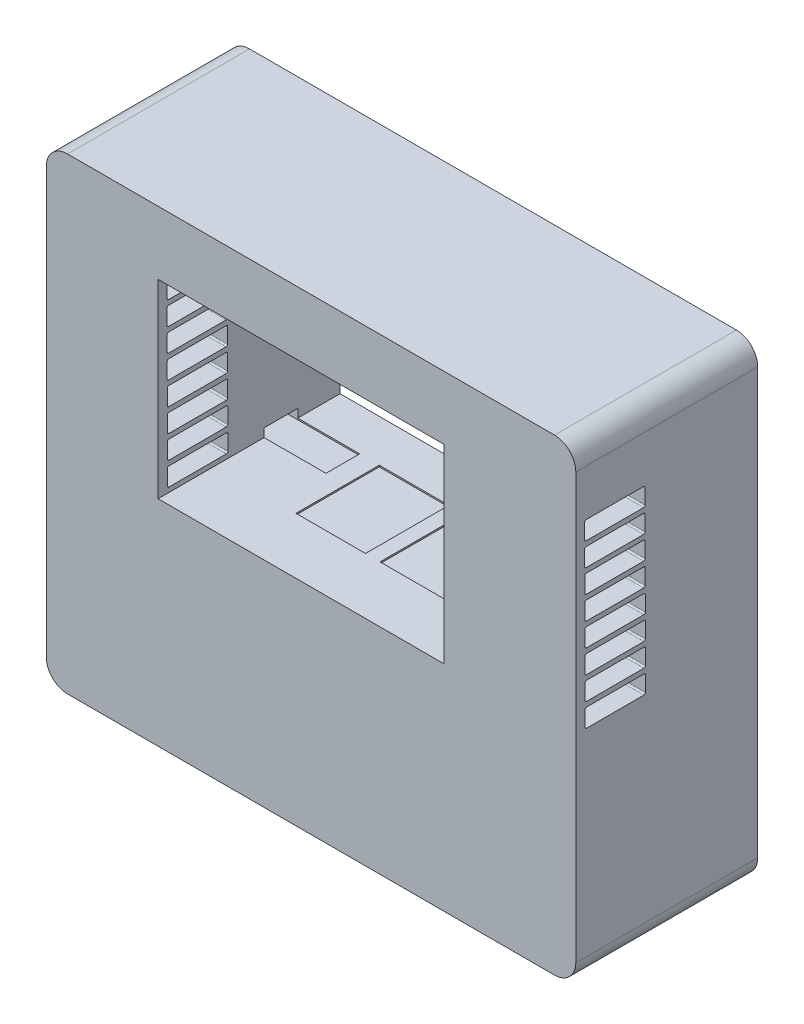
SolidWorks part; units mm, degrees
ref_plane "Front Plane" through (0, 0, 0) normal (0, 0, 1) x (1, 0, 0)
ref_plane "Top Plane" through (0, 0, 0) normal (0, 1, 0) x (1, 0, 0)
ref_plane "Right Plane" through (0, 0, 0) normal (1, 0, 0) x (0, 0, -1)
sketch "Sketch1" plane through (0, 0, 0) normal (0, 0, 1) x (1, 0, 0)
  line L4 (61.7, -0.1) -> (61.7, 38.3)
  line L5 (61.7, 38.3) -> (3.9, 38.3)
  line L6 (3.9, 38.3) -> (3.9, -0.1)
  line L7 (3.9, -0.1) -> (61.7, -0.1)
  line L8 (61.7, -0.1) -> (61.7, 38.3)
  line L9 (61.7, 38.3) -> (3.9, 38.3)
  line L10 (3.9, 38.3) -> (3.9, -0.1)
  line L11 (3.9, -0.1) -> (61.7, -0.1)
  line L12 (84, 51.09) -> (-14.4, 51.09)
  line L13 (-18.7, 46.79) -> (-18.7, -39.11)
  line L14 (-14.4, -43.41) -> (84, -43.41)
  line L15 (88.3, -39.11) -> (88.3, 46.79)
  line L16 (84, 51.09) -> (-14.4, 51.09)
  line L17 (-18.7, 46.79) -> (-18.7, -39.11)
  line L18 (-14.4, -43.41) -> (84, -43.41)
  line L19 (88.3, -39.11) -> (88.3, 46.79)
  arc A4 (88.3, 46.79) -> (84, 51.09) centre (84, 46.79) ccw
  arc A5 (-14.4, 51.09) -> (-18.7, 46.79) centre (-14.4, 46.79) ccw
  arc A6 (-18.7, -39.11) -> (-14.4, -43.41) centre (-14.4, -39.11) ccw
  arc A7 (84, -43.41) -> (88.3, -39.11) centre (84, -39.11) ccw
  arc A8 (88.3, 46.79) -> (84, 51.09) centre (84, 46.79) ccw
  arc A9 (-14.4, 51.09) -> (-18.7, 46.79) centre (-14.4, 46.79) ccw
  arc A10 (-18.7, -39.11) -> (-14.4, -43.41) centre (-14.4, -39.11) ccw
  arc A11 (84, -43.41) -> (88.3, -39.11) centre (84, -39.11) ccw
  dimension "D1" = 0
  dimension "D2" = 0
extrude "Boss-Extrude1" add sketch "Sketch1" against normal up to surface (36.766 mm away)
sketch "Sketch3" plane through (0, -0.4, 0) normal (0, -1, 0) x (1, 0, 0)
  line L0 (72.33, -24.7898) -> (72.33, -28.2198) construction
  line L1 (72.33, -28.2198) -> (81.22, -28.2198) construction
  line L2 (81.22, -28.2198) -> (81.22, -24.7898) construction
  line L3 (81.22, -24.7898) -> (72.33, -24.7898) construction
  line L4 (68.12, -28.296) -> (69.827, -28.296) construction
  line L5 (69.827, -28.296) -> (69.827, -14.646) construction
  line L6 (69.827, -14.646) -> (68.12, -14.646) construction
  line L7 (55.38, -28.296) -> (57.38, -28.296) construction
  line L8 (57.38, -14.646) -> (55.38, -14.646) construction
  line L9 (53.673, -14.646) -> (53.673, -28.296) construction
  line L10 (53.673, -28.296) -> (55.38, -28.296) construction
  line L11 (55.38, -14.646) -> (53.673, -14.646) construction
  line L12 (57.38, -28.296) -> (66.12, -28.296) construction
  line L13 (66.12, -14.646) -> (57.38, -14.646) construction
  line L14 (66.12, -28.296) -> (68.12, -28.296) construction
  line L15 (68.12, -14.646) -> (66.12, -14.646) construction
  line L16 (37.375, -11.3798) -> (37.375, -28.2198) construction
  line L17 (37.375, -28.2198) -> (51.425, -28.2198) construction
  line L18 (51.425, -28.2198) -> (51.425, -11.3798) construction
  line L19 (51.425, -11.3798) -> (37.375, -11.3798) construction
  line L20 (20.375, -11.3798) -> (20.375, -28.2198) construction
  line L21 (20.375, -28.2198) -> (34.425, -28.2198) construction
  line L22 (34.425, -28.2198) -> (34.425, -11.3798) construction
  line L23 (34.425, -11.3798) -> (20.375, -11.3798) construction
  line L24 (-1.288, -21.4098) -> (-1.288, -28.2198) construction
  line L25 (-1.288, -28.2198) -> (16.408, -28.2198) construction
  line L26 (16.408, -28.2198) -> (16.408, -21.4098) construction
  line L27 (16.408, -21.4098) -> (-1.288, -21.4098) construction
  line L28 (-13.85, -17.296) -> (-13.85, -28.296) construction
  line L29 (-13.85, -28.296) -> (-4.55, -28.296) construction
  line L30 (-4.55, -28.296) -> (-4.55, -17.296) construction
  line L31 (-4.55, -17.296) -> (-13.85, -17.296) construction
  line L32 (72.33, -24.7898) -> (72.33, -28.2198)
  line L33 (72.33, -28.2198) -> (81.22, -28.2198)
  line L34 (81.22, -28.2198) -> (81.22, -24.7898)
  line L35 (81.22, -24.7898) -> (72.33, -24.7898)
  line L36 (68.12, -28.296) -> (69.827, -28.296)
  line L37 (69.827, -28.296) -> (69.827, -14.646)
  line L38 (69.827, -14.646) -> (68.12, -14.646)
  line L39 (55.38, -28.296) -> (57.38, -28.296)
  line L40 (57.38, -14.646) -> (55.38, -14.646)
  line L41 (53.673, -14.646) -> (53.673, -28.296)
  line L42 (53.673, -28.296) -> (55.38, -28.296)
  line L43 (55.38, -14.646) -> (53.673, -14.646)
  line L44 (57.38, -28.296) -> (66.12, -28.296)
  line L45 (66.12, -14.646) -> (57.38, -14.646)
  line L46 (66.12, -28.296) -> (68.12, -28.296)
  line L47 (68.12, -14.646) -> (66.12, -14.646)
  line L48 (37.375, -11.3798) -> (37.375, -28.2198)
  line L49 (37.375, -28.2198) -> (51.425, -28.2198)
  line L50 (51.425, -28.2198) -> (51.425, -11.3798)
  line L51 (51.425, -11.3798) -> (37.375, -11.3798)
  line L52 (20.375, -11.3798) -> (20.375, -28.2198)
  line L53 (20.375, -28.2198) -> (34.425, -28.2198)
  line L54 (34.425, -28.2198) -> (34.425, -11.3798)
  line L55 (34.425, -11.3798) -> (20.375, -11.3798)
  line L56 (-1.288, -21.4098) -> (-1.288, -28.2198)
  line L57 (-1.288, -28.2198) -> (16.408, -28.2198)
  line L58 (16.408, -28.2198) -> (16.408, -21.4098)
  line L59 (16.408, -21.4098) -> (-1.288, -21.4098)
  line L60 (-13.85, -17.296) -> (-13.85, -28.296)
  line L61 (-13.85, -28.296) -> (-4.55, -28.296)
  line L62 (-4.55, -28.296) -> (-4.55, -17.296)
  line L63 (-4.55, -17.296) -> (-13.85, -17.296)
extrude "Cut-Extrude1" cut sketch "Sketch3" against normal blind 2
sketch "Sketch5" plane through (-18.7, 0, 0) normal (-1, 0, 0) x (0, 0, 1)
  line L0 (-1.8, 29.3) -> (-1.8, 32.4) construction
  line L1 (-13.7, 29) -> (-2.1, 29) construction
  line L2 (-14, 32.4) -> (-14, 29.3) construction
  line L3 (-2.1, 32.7) -> (-13.7, 32.7) construction
  line L4 (-1.8, 34) -> (-1.8, 37.1) construction
  line L5 (-13.7, 33.7) -> (-2.1, 33.7) construction
  line L6 (-14, 37.1) -> (-14, 34) construction
  line L7 (-2.1, 37.4) -> (-13.7, 37.4) construction
  line L8 (-1.8, 29.3) -> (-1.8, 32.4)
  line L9 (-13.7, 29) -> (-2.1, 29)
  line L10 (-14, 32.4) -> (-14, 29.3)
  line L11 (-2.1, 32.7) -> (-13.7, 32.7)
  line L12 (-1.8, 34) -> (-1.8, 37.1)
  line L13 (-13.7, 33.7) -> (-2.1, 33.7)
  line L14 (-14, 37.1) -> (-14, 34)
  line L15 (-2.1, 37.4) -> (-13.7, 37.4)
  line L16 (-1.8281, 19.9183) -> (-1.8281, 23.0183)
  line L17 (-13.7281, 19.6183) -> (-2.1281, 19.6183)
  line L18 (-14.0281, 23.0183) -> (-14.0281, 19.9183)
  line L19 (-2.1281, 23.3183) -> (-13.7281, 23.3183)
  line L20 (-1.8281, 24.6183) -> (-1.8281, 27.7183)
  line L21 (-13.7281, 24.3183) -> (-2.1281, 24.3183)
  line L22 (-14.0281, 27.7183) -> (-14.0281, 24.6183)
  line L23 (-2.1281, 28.0183) -> (-13.7281, 28.0183)
  line L24 (-1.8561, 10.5367) -> (-1.8561, 13.6367)
  line L25 (-13.7561, 10.2367) -> (-2.1561, 10.2367)
  line L26 (-14.0561, 13.6367) -> (-14.0561, 10.5367)
  line L27 (-2.1561, 13.9367) -> (-13.7561, 13.9367)
  line L28 (-1.8561, 15.2367) -> (-1.8561, 18.3367)
  line L29 (-13.7561, 14.9367) -> (-2.1561, 14.9367)
  line L30 (-14.0561, 18.3367) -> (-14.0561, 15.2367)
  line L31 (-2.1561, 18.6367) -> (-13.7561, 18.6367)
  line L32 (-1.8842, 1.155) -> (-1.8842, 4.255)
  line L33 (-13.7842, 0.855) -> (-2.1842, 0.855)
  line L34 (-14.0842, 4.255) -> (-14.0842, 1.155)
  line L35 (-2.1842, 4.555) -> (-13.7842, 4.555)
  line L36 (-1.8842, 5.855) -> (-1.8842, 8.955)
  line L37 (-13.7842, 5.555) -> (-2.1842, 5.555)
  line L38 (-14.0842, 8.955) -> (-14.0842, 5.855)
  line L39 (-2.1842, 9.255) -> (-13.7842, 9.255)
  arc A0 (-2.1, 29) -> (-1.8, 29.3) centre (-2.1, 29.3) ccw construction
  arc A1 (-1.8, 32.4) -> (-2.1, 32.7) centre (-2.1, 32.4) ccw construction
  arc A2 (-14, 29.3) -> (-13.7, 29) centre (-13.7, 29.3) ccw construction
  arc A3 (-13.7, 32.7) -> (-14, 32.4) centre (-13.7, 32.4) ccw construction
  arc A4 (-2.1, 33.7) -> (-1.8, 34) centre (-2.1, 34) ccw construction
  arc A5 (-1.8, 37.1) -> (-2.1, 37.4) centre (-2.1, 37.1) ccw construction
  arc A6 (-14, 34) -> (-13.7, 33.7) centre (-13.7, 34) ccw construction
  arc A7 (-13.7, 37.4) -> (-14, 37.1) centre (-13.7, 37.1) ccw construction
  arc A8 (-2.1, 29) -> (-1.8, 29.3) centre (-2.1, 29.3) ccw
  arc A9 (-1.8, 32.4) -> (-2.1, 32.7) centre (-2.1, 32.4) ccw
  arc A10 (-14, 29.3) -> (-13.7, 29) centre (-13.7, 29.3) ccw
  arc A11 (-13.7, 32.7) -> (-14, 32.4) centre (-13.7, 32.4) ccw
  arc A12 (-2.1, 33.7) -> (-1.8, 34) centre (-2.1, 34) ccw
  arc A13 (-1.8, 37.1) -> (-2.1, 37.4) centre (-2.1, 37.1) ccw
  arc A14 (-14, 34) -> (-13.7, 33.7) centre (-13.7, 34) ccw
  arc A15 (-13.7, 37.4) -> (-14, 37.1) centre (-13.7, 37.1) ccw
  arc A16 (-2.1281, 19.6183) -> (-1.8281, 19.9183) centre (-2.1281, 19.9183) ccw
  arc A17 (-1.8281, 23.0183) -> (-2.1281, 23.3183) centre (-2.1281, 23.0183) ccw
  arc A18 (-14.0281, 19.9183) -> (-13.7281, 19.6183) centre (-13.7281, 19.9183) ccw
  arc A19 (-13.7281, 23.3183) -> (-14.0281, 23.0183) centre (-13.7281, 23.0183) ccw
  arc A20 (-2.1281, 24.3183) -> (-1.8281, 24.6183) centre (-2.1281, 24.6183) ccw
  arc A21 (-1.8281, 27.7183) -> (-2.1281, 28.0183) centre (-2.1281, 27.7183) ccw
  arc A22 (-14.0281, 24.6183) -> (-13.7281, 24.3183) centre (-13.7281, 24.6183) ccw
  arc A23 (-13.7281, 28.0183) -> (-14.0281, 27.7183) centre (-13.7281, 27.7183) ccw
  arc A24 (-2.1561, 10.2367) -> (-1.8561, 10.5367) centre (-2.1561, 10.5367) ccw
  arc A25 (-1.8561, 13.6367) -> (-2.1561, 13.9367) centre (-2.1561, 13.6367) ccw
  arc A26 (-14.0561, 10.5367) -> (-13.7561, 10.2367) centre (-13.7561, 10.5367) ccw
  arc A27 (-13.7561, 13.9367) -> (-14.0561, 13.6367) centre (-13.7561, 13.6367) ccw
  arc A28 (-2.1561, 14.9367) -> (-1.8561, 15.2367) centre (-2.1561, 15.2367) ccw
  arc A29 (-1.8561, 18.3367) -> (-2.1561, 18.6367) centre (-2.1561, 18.3367) ccw
  arc A30 (-14.0561, 15.2367) -> (-13.7561, 14.9367) centre (-13.7561, 15.2367) ccw
  arc A31 (-13.7561, 18.6367) -> (-14.0561, 18.3367) centre (-13.7561, 18.3367) ccw
  arc A32 (-2.1842, 0.855) -> (-1.8842, 1.155) centre (-2.1842, 1.155) ccw
  arc A33 (-1.8842, 4.255) -> (-2.1842, 4.555) centre (-2.1842, 4.255) ccw
  arc A34 (-14.0842, 1.155) -> (-13.7842, 0.855) centre (-13.7842, 1.155) ccw
  arc A35 (-13.7842, 4.555) -> (-14.0842, 4.255) centre (-13.7842, 4.255) ccw
  arc A36 (-2.1842, 5.555) -> (-1.8842, 5.855) centre (-2.1842, 5.855) ccw
  arc A37 (-1.8842, 8.955) -> (-2.1842, 9.255) centre (-2.1842, 8.955) ccw
  arc A38 (-14.0842, 5.855) -> (-13.7842, 5.555) centre (-13.7842, 5.855) ccw
  arc A39 (-13.7842, 9.255) -> (-14.0842, 8.955) centre (-13.7842, 8.955) ccw
  dimension "D1" = 4
extrude "Cut-Extrude2" cut sketch "Sketch5" against normal blind 145 and the other way blind 51
